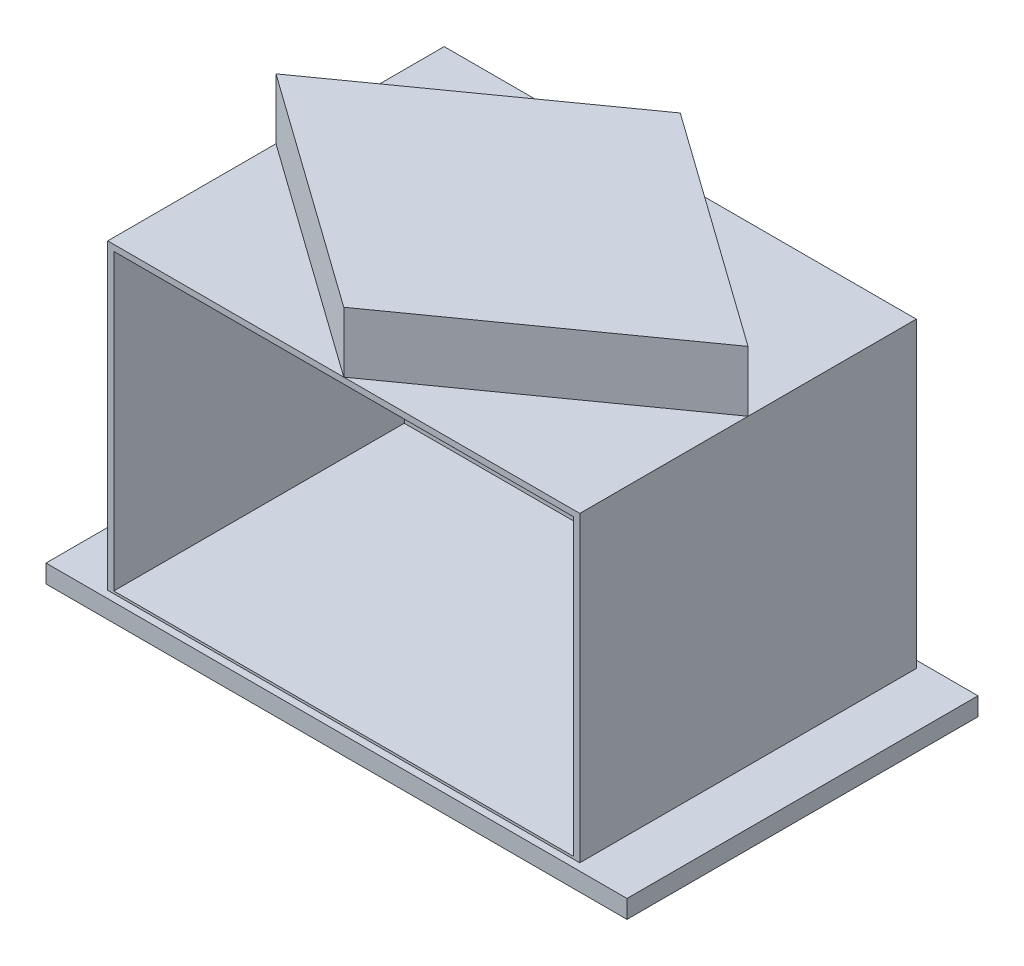
SolidWorks part; units mm, degrees
ref_plane "前视基准面" through (0, 0, 0) normal (0, 0, 1) x (1, 0, 0)
ref_plane "上视基准面" through (0, 0, 0) normal (0, 1, 0) x (1, 0, 0)
ref_plane "右视基准面" through (0, 0, 0) normal (1, 0, 0) x (0, 0, -1)
other "Configuration Table"
sketch "草图1" plane through (0, 0, 0) normal (0, 1, 0) x (1, 0, 0)
  line L1 (-240, -145) -> (240, -145)
  line L2 (-240, -145) -> (-240, 145)
  line L3 (-240, 145) -> (240, 145)
  line L4 (240, -145) -> (240, 145)
  line L5 (-240, -145) -> (240, 145) construction
  line L6 (-240, 145) -> (240, -145) construction
  point P0 (0, 0)
extrude "凸台-拉伸1" add sketch "草图1" against normal blind 15
sketch "草图2" plane through (0, 0, 0) normal (0, 1, 0) x (1, 0, 0)
  line L1 (-195, -39) -> (195, -39)
  line L2 (-195, -39) -> (-195, 139)
  line L3 (-195, 139) -> (195, 139)
  line L4 (195, -39) -> (195, 139)
  line L5 (-195, -39) -> (195, 139) construction
  line L6 (-195, 139) -> (195, -39) construction
  point P0 (0, 50)
extrude "凸台-拉伸2" add sketch "草图2" along normal blind 250
sketch "草图7" plane through (0, 0, 39) normal (0, 0, 1) x (1, 0, 0)
  line L0 (-195, 250) -> (-195, 0)
  line L1 (-195, 0) -> (195, 0)
  line L2 (195, 0) -> (195, 250)
  line L3 (195, 250) -> (-195, 250)
extrude "凸台-拉伸7" add sketch "草图7" along normal blind 100
sketch "草图8" plane through (0, 0, 139) normal (0, 0, 1) x (1, 0, 0)
  line L0 (-190, 245) -> (190, 245)
  line L1 (190, 245) -> (190, 2)
  line L2 (190, 2) -> (-190, 2)
  line L3 (-190, 2) -> (-190, 245)
  line L4 (-195, 0) -> (195, 0) construction
  line L5 (-195, 250) -> (-195, 0) construction
  line L6 (195, 0) -> (195, 250) construction
  line L7 (195, 250) -> (-195, 250) construction
  dimension "D1" = 2
  dimension "D2" = 5
  dimension "D3" = 5
  dimension "D4" = 5
extrude "切除-拉伸1" cut sketch "草图8" against normal blind 240
sketch "草图10" plane through (0, 250, 0) normal (0, 1, 0) x (1, 0, 0)
  line L0 (0, 139) -> (-195, 0)
  line L1 (195, 139) -> (-195, 139) construction
  line L2 (-195, 139) -> (-195, -139) construction
  line L3 (-195, 0) -> (0, -139)
  line L4 (195, -139) -> (-195, -139) construction
  line L5 (0, -139) -> (195, 0)
  line L6 (195, -139) -> (195, 139) construction
  line L7 (195, 0) -> (0, 139)
extrude "凸台-拉伸8" add sketch "草图10" along normal blind 50
